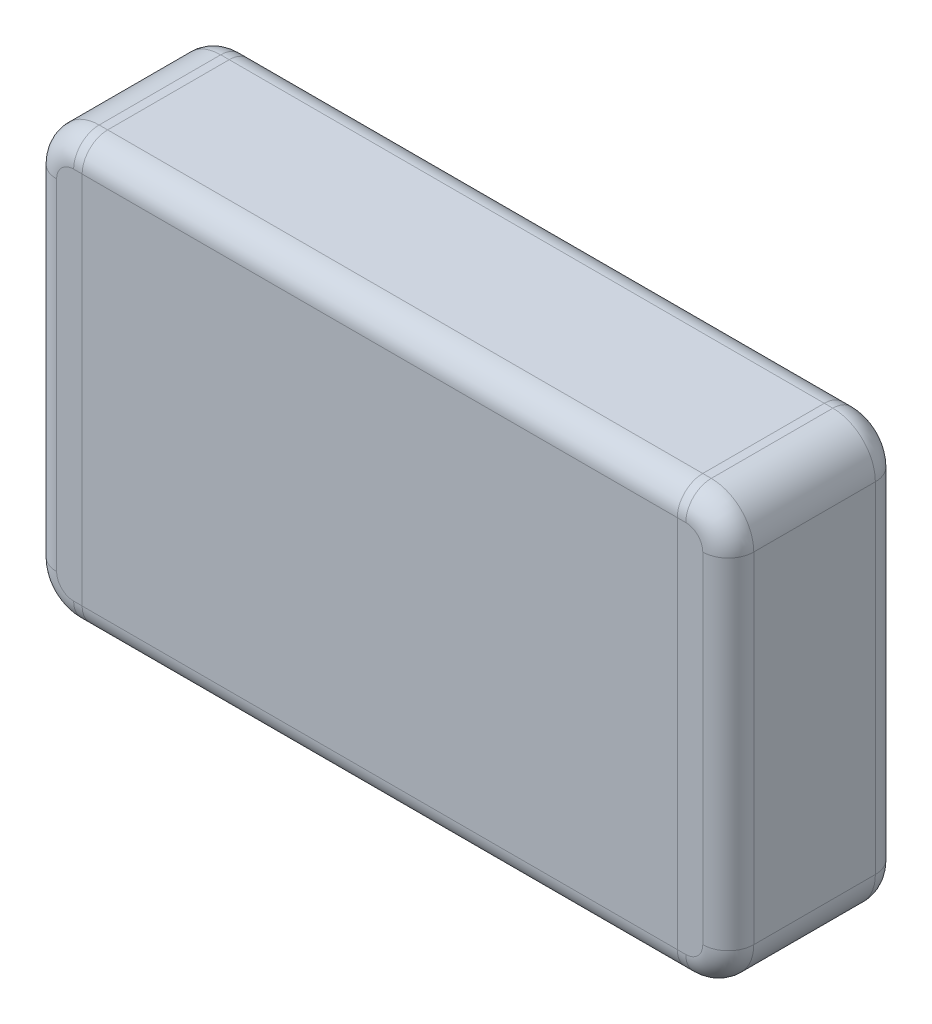
SolidWorks part; units mm, degrees
ref_plane "Front" through (0, 0, 0) normal (0, 0, 1) x (1, 0, 0)
ref_plane "Top" through (0, 0, 0) normal (0, 1, 0) x (1, 0, 0)
ref_plane "Right" through (0, 0, 0) normal (1, 0, 0) x (0, 0, -1)
sketch "Эскиз1" plane through (0, 0, 0) normal (0, 0, 1) x (1, 0, 0)
  line L1 (-3.5, -2.5) -> (3.5, -2.5)
  line L2 (-3.5, -2.5) -> (-3.5, 2.5)
  line L3 (-3.5, 2.5) -> (3.5, 2.5)
  line L4 (3.5, -2.5) -> (3.5, 2.5)
  line L5 (-3.5, -2.5) -> (3.5, 2.5) construction
  line L6 (-3.5, 2.5) -> (3.5, -2.5) construction
  point P0 (0, 0)
  dimension "D1" = 5
  dimension "D2" = 7
extrude "Бобышка-Вытянуть1" add sketch "Эскиз1" along normal blind 2.03
sketch "Эскиз2" plane through (0, 0, 0) normal (0, 0, -1) x (-1, 0, 0)
  line L0 (3.5, -2.5) -> (3.6, -2.5)
  line L1 (4.1, -2) -> (4.1, 2)
  line L2 (3.6, 2.5) -> (3.5, 2.5)
  line L3 (3.5, 2.5) -> (3.5, -2.5)
  line L4 (3.5, 2.5) -> (3.5, -2.5) construction
  arc A0 (3.6, -2.5) -> (4.1, -2) centre (3.6, -2) ccw
  arc A1 (4.1, 2) -> (3.6, 2.5) centre (3.6, 2) ccw
  dimension "D1" = 0.6
  dimension "D2" = 0.5
extrude "Бобышка-Вытянуть2" add sketch "Эскиз2" against normal up to vertex (2.03 mm away) separate body
fillet "Скругление2" radius 0.3 4 edges at (0, -2.5, 2.03) (0, -2.5, 0) (0, 2.5, 0) (0, 2.5, 2.03)
fillet "Скругление1" radius 0.3 10 edges at (-3.55, -2.5, 0) (-3.9536, -2.3536, 0) (-3.55, 2.5, 0) (-3.9536, 2.3536, 0) (-3.55, -2.5, 2.03) (-3.9536, -2.3536, 2.03) (-3.55, 2.5, 2.03) (-3.9536, 2.3536, 2.03) (-4.1, 0, 0) (-4.1, 0, 2.03)
mirror "Зеркальное отражение3" about plane through (0, 0, 0) normal (1, 0, 0) of bodies 102
